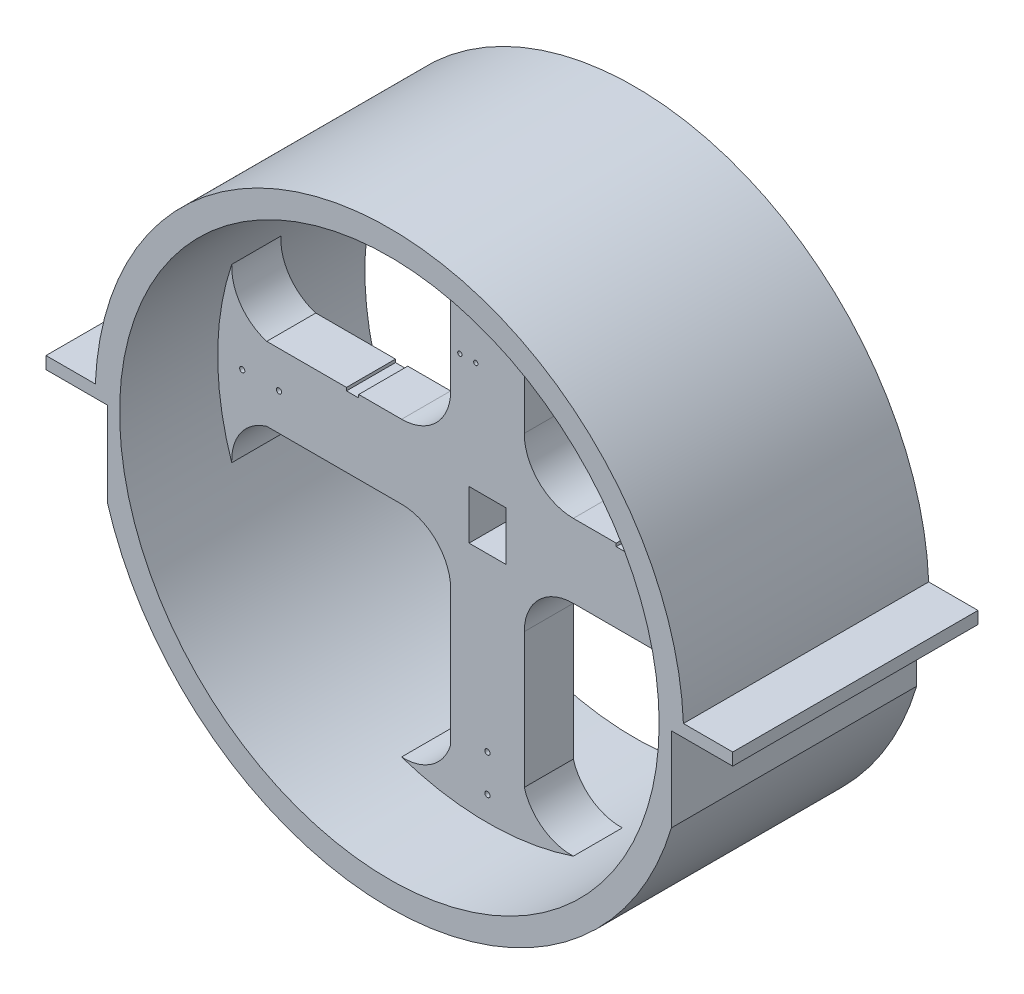
SolidWorks part; units mm, degrees
material "6061 Alloy"
ref_plane "Front Plane" through (0, 0, 0) normal (0, 0, 1) x (1, 0, 0)
ref_plane "Top Plane" through (0, 0, 0) normal (0, 1, 0) x (1, 0, 0)
ref_plane "Right Plane" through (0, 0, 0) normal (1, 0, 0) x (0, 0, -1)
sketch "Sketch1" plane through (0, 0, 0) normal (0, 0, 1) x (1, 0, 0)
  circle A0 centre (0, 0) radius 152.4
  circle A1 centre (0, 0) radius 139.7
  dimension "D1" = 304.8
  dimension "D2" = 279.4
extrude "Boss-Extrude1" add sketch "Sketch1" along normal mid plane 127
sketch "Sketch2" plane through (0, 0, 0) normal (0, 0, 1) x (1, 0, 0)
  line L0 (-114.3, 19.05) -> (-138.7192, 19.05)
  line L1 (-147.1918, -19.05) -> (147.1918, -19.05)
  line L2 (-147.1918, -19.05) -> (-147.1918, 19.05)
  line L3 (-147.1918, 19.05) -> (147.1918, 19.05)
  line L4 (147.1918, -19.05) -> (147.1918, 19.05)
  line L5 (-147.1918, -19.05) -> (147.1918, 19.05) construction
  line L6 (-147.1918, 19.05) -> (147.1918, -19.05) construction
  line L7 (19.05, -143.9568) -> (-19.05, -143.9568)
  line L8 (19.05, -143.9568) -> (19.05, 143.9568)
  line L9 (19.05, 143.9568) -> (-19.05, 143.9568)
  line L10 (-19.05, -143.9568) -> (-19.05, 143.9568)
  line L11 (19.05, -143.9568) -> (-19.05, 143.9568) construction
  line L12 (19.05, 143.9568) -> (-19.05, -143.9568) construction
  line L15 (-44.45, 19.05) -> (-19.05, 19.05)
  line L16 (-19.05, 44.45) -> (-19.05, 19.05)
  line L17 (-132.4254, 44.4927) -> (-143.3503, 19.05)
  line L18 (-143.3503, 19.05) -> (-138.7192, 19.05)
  line L19 (-138.7192, 19.05) -> (-143.3503, 19.05)
  line L20 (-19.05, 114.3) -> (-19.05, 143.9568)
  line L21 (-44.45, 132.4398) -> (-19.05, 143.9568)
  line L22 (44.45, 19.05) -> (19.05, 19.05)
  line L23 (19.05, 44.45) -> (19.05, 19.05)
  line L24 (19.05, 143.3503) -> (19.05, 138.7192)
  line L25 (19.05, 114.3) -> (19.05, 138.7192)
  line L26 (44.4927, 132.4254) -> (19.05, 143.3503)
  line L27 (114.3, 19.05) -> (143.9568, 19.05)
  line L28 (132.4398, 44.45) -> (143.9568, 19.05)
  line L29 (19.05, -44.45) -> (19.05, -19.05)
  line L30 (44.45, -19.05) -> (19.05, -19.05)
  line L31 (143.3503, -19.05) -> (138.7192, -19.05)
  line L32 (114.3, -19.05) -> (138.7192, -19.05)
  line L33 (132.4254, -44.4927) -> (143.3503, -19.05)
  line L34 (19.05, -114.3) -> (19.05, -143.9568)
  line L35 (44.45, -132.4398) -> (19.05, -143.9568)
  line L36 (-44.45, -19.05) -> (-19.05, -19.05)
  line L37 (-19.05, -44.45) -> (-19.05, -19.05)
  line L38 (-19.05, -143.3503) -> (-19.05, -138.7192)
  line L39 (-19.05, -114.3) -> (-19.05, -138.7192)
  line L40 (-44.4927, -132.4254) -> (-19.05, -143.3503)
  line L41 (-114.3, -19.05) -> (-143.9568, -19.05)
  line L42 (-132.4398, -44.45) -> (-143.9568, -19.05)
  arc A1 (-44.45, 19.05) -> (-19.05, 44.45) centre (-44.45, 44.45) ccw
  arc A2 (-114.3, 19.05) -> (-132.4254, 44.4927) centre (-107.0492, 43.3931) cw
  circle A3 centre (0, 0) radius 139.7 construction
  arc A5 (-19.05, 114.3) -> (-44.45, 132.4398) centre (-43.3968, 107.0616) ccw
  arc A6 (19.05, 44.45) -> (44.45, 19.05) centre (44.45, 44.45) ccw
  arc A7 (19.05, 114.3) -> (44.4927, 132.4254) centre (43.3931, 107.0492) cw
  arc A8 (114.3, 19.05) -> (132.4398, 44.45) centre (107.0616, 43.3968) ccw
  arc A9 (44.45, -19.05) -> (19.05, -44.45) centre (44.45, -44.45) ccw
  arc A10 (114.3, -19.05) -> (132.4254, -44.4927) centre (107.0492, -43.3931) cw
  arc A11 (19.05, -114.3) -> (44.45, -132.4398) centre (43.3968, -107.0616) ccw
  arc A12 (-19.05, -44.45) -> (-44.45, -19.05) centre (-44.45, -44.45) ccw
  arc A13 (-19.05, -114.3) -> (-44.4927, -132.4254) centre (-43.3931, -107.0492) cw
  arc A14 (-114.3, -19.05) -> (-132.4398, -44.45) centre (-107.0616, -43.3968) ccw
  point P0 (0, 0)
  point P6 (0, 0)
  point P67 (0, 0)
  dimension "D3" = 25.4
  dimension "D5" = 25.4
  dimension "D1" = 38.1
  dimension "D2" = 38.1
  dimension "D4" = 114.3
  dimension "D6" = 114.3
  dimension "D7" = 4
extrude "Boss-Extrude2" add sketch "Sketch2" along normal mid plane 25.4 contours L1 L10 L3 L2 | L10 L1 L8 L3 | L10 L3 L8 L9 | L8 L1 L4 L3 | L10 L7 L8 L1 | A14 L1 L42 | L10 A13 L40 | A11 L8 L35 | A9 L1 L8 | L1 A10 L33 | A8 L3 L28 | L8 A7 L26 | A5 L10 L21 | L0 A2 L17 L3 | A1 L3 L10 | A6 L8 L3 | A12 L10 L1
sketch "Sketch4" plane through (0, 0, 0) normal (0, 0, 1) x (1, 0, 0)
  line L0 (-9.525, -19.05) -> (-9.525, 0)
  line L5 (-9.525, -19.05) -> (9.525, -19.05)
  line L6 (-9.525, 0) -> (9.525, 0)
  line L7 (9.525, -19.05) -> (9.525, 0)
  line L8 (-9.525, -19.05) -> (9.525, 0) construction
  line L9 (-9.525, 0) -> (9.525, -19.05) construction
  point P1 (0, -9.525)
  dimension "D1" = 19.05
  dimension "D2" = 19.05
  dimension "D3" = 9.525
  dimension "D4" = 0
extrude "Cut-Extrude3" cut sketch "Sketch4" against normal through all both and the other way through all
sketch "Sketch7" plane through (0, 0, 12.7) normal (0, 0, 1) x (1, 0, 0)
  line L0 (-9.525, 0) -> (9.525, 0)
  line L1 (-9.525, 0) -> (-9.525, 6.35)
  line L2 (9.525, 0) -> (9.525, 6.35)
  line L3 (-9.525, 6.35) -> (9.525, 6.35)
  line L4 (9.525, 0) -> (-9.525, 0) construction
  line L5 (-9.525, -19.05) -> (9.525, -19.05) construction
  dimension "D1" = 25.4
extrude "Cut-Extrude4" cut sketch "Sketch7" against normal through all
sketch "Sketch8" plane through (0, 0, 63.5) normal (0, 0, 1) x (1, 0, 0)
  line L0 (-146.05, 0) -> (-163.2527, 0)
  line L1 (-146.05, 0) -> (-146.05, -50.8)
  line L2 (-163.2527, 0) -> (-163.2527, -50.8)
  line L3 (-146.05, -50.8) -> (-163.2527, -50.8)
  circle A0 centre (0, 0) radius 152.4 construction
  dimension "D1" = 50.8
  dimension "D2" = 146.05
extrude "Cut-Extrude5" cut sketch "Sketch8" against normal through all
mirror "Mirror1" about plane through (0, 0, 0) normal (1, 0, 0) of "Cut-Extrude5"
sketch "Sketch9" plane through (0, 0, 63.5) normal (0, 0, 1) x (1, 0, 0)
  line L1 (146.05, 0) -> (177.8, 0)
  line L2 (146.05, 0) -> (146.05, 6.35)
  line L3 (146.05, 6.35) -> (177.8, 6.35)
  line L4 (177.8, 0) -> (177.8, 6.35)
  dimension "D1" = 6.35
  dimension "D2" = 31.75
extrude "Boss-Extrude3" add sketch "Sketch9" against normal blind 127
mirror "Mirror2" about plane through (0, 0, 0) normal (1, 0, 0) of "Boss-Extrude3"
sketch "Sketch10" plane through (0, 0, 12.7) normal (0, 0, 1) x (1, 0, 0)
  line L0 (-114.3, 19.05) -> (-44.45, 19.05) construction
  line L1 (-73.025, 19.05) -> (-66.675, 19.05)
  line L2 (-73.025, 19.05) -> (-73.025, 17.4625)
  line L3 (-73.025, 17.4625) -> (-66.675, 17.4625)
  line L4 (-66.675, 19.05) -> (-66.675, 17.4625)
  line L6 (-9.525, 6.35) -> (-9.525, -19.05) construction
  dimension "D1" = 1.5875
  dimension "D2" = 6.35
  dimension "D3" = 57.15
extrude "Cut-Extrude6" cut sketch "Sketch10" against normal through all
mirror "Mirror3" about plane through (0, 0, 0) normal (1, 0, 0) of "Cut-Extrude6"
hole_wizard "#4-40 Tapped Hole1" positions "Sketch11" profile "Sketch12" tap size "#4-40" standard "ANSI Inch" end condition through all
sketch "Sketch11" plane through (0, 0, 12.7) normal (0, 0, 1) x (1, 0, 0)
  line L0 (-19.05, 44.45) -> (-19.05, 114.3) construction
  line L1 (73.025, 19.05) -> (114.3, 19.05) construction
  point P0 (-14.2875, 63.5)
  point P2 (-6.0325, 63.5)
  point P4 (88.9, 14.2875)
  point P6 (88.9, 6.0325)
  dimension "D1" = 63.5
  dimension "D2" = 63.5
  dimension "D3" = 8.255
  dimension "D4" = 8.255
  dimension "D5" = 88.9
  dimension "D6" = 4.7625
  dimension "D7" = 4.7625
sketch "Sketch12" plane through (-14.2875, 63.5, 12.7) normal (1, 0, 0) x (0, -1, 0)
  line L0 (0, 0) -> (0, 76.2)
  line L1 (0, 76.2) -> (1.1303, 76.2)
  line L2 (1.1303, 76.2) -> (1.1303, 0)
  line L5 (1.1303, 0) -> (0, 0)
  line L11 (0, -6.35) -> (0, 107.95) construction
  dimension "Thru Tap Drill Dia." = 2.2606
  dimension "Thru Tap Drill Depth" = 76.2
cosmetic thread "Hole Thread1" parameters "D2"=2.8448
cosmetic thread "Hole Thread2" parameters "D2"=2.8448
cosmetic thread "Hole Thread3" parameters "D2"=2.8448
cosmetic thread "Hole Thread4" parameters "D2"=2.8448
hole_wizard "#6-32 Tapped Hole1" positions "Sketch13" profile "Sketch14" tap size "#6-32" standard "ANSI Inch" end condition through all
sketch "Sketch13" plane through (0, 0, 12.7) normal (0, 0, 1) x (1, 0, 0)
  point P0 (-107.95, 0)
  point P2 (-127, 0)
  dimension "D1" = 107.95
  dimension "D2" = 19.05
sketch "Sketch14" plane through (-107.95, 0, 12.7) normal (1, 0, 0) x (0, -1, 0)
  line L0 (0, 0) -> (0, 76.2)
  line L1 (0, 76.2) -> (1.3525, 76.2)
  line L2 (1.3525, 76.2) -> (1.3525, 0)
  line L5 (1.3525, 0) -> (0, 0)
  line L11 (0, -6.35) -> (0, 107.95) construction
  dimension "Thru Tap Drill Dia." = 2.7051
  dimension "Thru Tap Drill Depth" = 76.2
cosmetic thread "Hole Thread5" parameters "D2"=3.5052
cosmetic thread "Hole Thread6" parameters "D2"=3.5052
pattern_circular "CirPattern1" count 4 every 90 about axis through (0, 0, 0) along (0, 0, 1) of "#6-32 Tapped Hole1"
